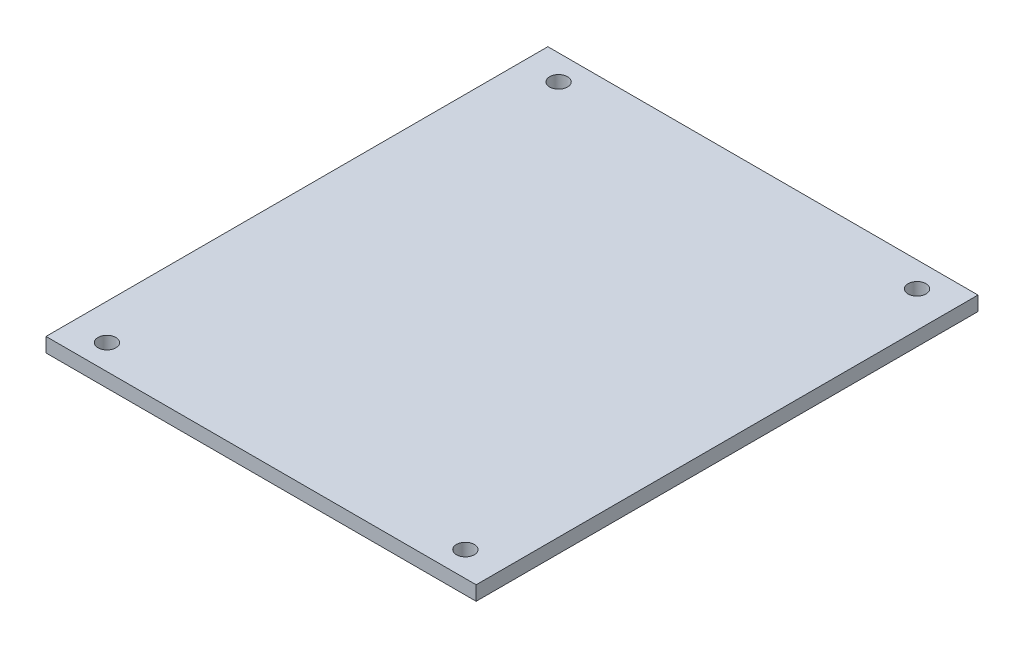
SolidWorks part; units mm, degrees
material "1060 Alloy"
ref_plane "Front Plane" through (0, 0, 0) normal (0, 0, 1) x (1, 0, 0)
ref_plane "Top Plane" through (0, 0, 0) normal (0, 1, 0) x (1, 0, 0)
ref_plane "Right Plane" through (0, 0, 0) normal (1, 0, 0) x (0, 0, -1)
sketch "Sketch1" plane through (0, 0, 0) normal (0, 1, 0) x (1, 0, 0)
  line L1 (-60, -70) -> (60, -70)
  line L2 (-60, -70) -> (-60, 70)
  line L3 (-60, 70) -> (60, 70)
  line L4 (60, -70) -> (60, 70)
  line L5 (-60, -70) -> (60, 70) construction
  line L6 (-60, 70) -> (60, -70) construction
  point P0 (0, 0)
  dimension "D1" = 140
  dimension "D2" = 120
extrude "Boss-Extrude1" add sketch "Sketch1" along normal blind 4
sketch "Sketch2" plane through (0, 4, 0) normal (0, 1, 0) x (1, 0, 0)
  line L0 (60, -70) -> (60, 70) construction
  line L1 (60, 50) -> (48, 50)
  line L2 (60, 50) -> (60, 27)
  line L3 (60, 27) -> (48, 27)
  line L4 (48, 50) -> (48, 27)
  line L5 (-60, 70) -> (-60, -70) construction
  line L6 (-60, 50) -> (-48, 50)
  line L7 (-60, 50) -> (-60, 27)
  line L8 (-60, 27) -> (-48, 27)
  line L9 (-48, 50) -> (-48, 27)
  line L10 (-48, 0) -> (0, 0) construction
  line L19 (60, -27) -> (48, -27)
  line L20 (60, -27) -> (60, -50)
  line L21 (60, -50) -> (48, -50)
  line L22 (48, -27) -> (48, -50)
  line L23 (-60, -27) -> (-48, -27)
  line L24 (-60, -27) -> (-60, -50)
  line L25 (-60, -50) -> (-48, -50)
  line L26 (-48, -27) -> (-48, -50)
  line L27 (0, 0) -> (48, 0) construction
  line L28 (-54, 52.65) -> (-54, 50) construction
  line L29 (-60, -70) -> (60, -70) construction
  line L30 (60, 70) -> (-60, 70) construction
  line L31 (-54, 24.35) -> (-54, 27) construction
  line L32 (-60, 17) -> (-48, 17)
  line L33 (-60, 17) -> (-60, -17)
  line L34 (-60, -17) -> (-48, -17)
  line L35 (-48, 17) -> (-48, -17)
  line L36 (60, 17) -> (48, 17)
  line L37 (60, 17) -> (60, -17)
  line L38 (60, -17) -> (48, -17)
  line L39 (48, 17) -> (48, -17)
  line L40 (-54, -24.35) -> (-54, -27) construction
  line L41 (-54, -50) -> (-54, -52.65) construction
  line L42 (54, 52.65) -> (54, 50) construction
  line L43 (54, 24.35) -> (54, 27) construction
  line L44 (54, -24.35) -> (54, -27) construction
  line L45 (54, -50) -> (54, -52.65) construction
  circle A2 centre (-54, 52.65) radius 1.1
  circle A3 centre (-54, 24.35) radius 1.1
  circle A4 centre (-54, -24.35) radius 1.1
  circle A5 centre (-54, -52.65) radius 1.1
  circle A6 centre (54, 52.65) radius 1.1
  circle A7 centre (54, 24.35) radius 1.1
  circle A8 centre (54, -24.35) radius 1.1
  circle A9 centre (54, -52.65) radius 1.1
  circle A10 centre (-50, 63) radius 2.5
  circle A11 centre (50, 63) radius 2.5
  circle A12 centre (50, -63) radius 2.5
  circle A13 centre (-50, -63) radius 2.5
  dimension "D6" = 2.2
  dimension "D15" = 5
  dimension "D1" = 23
  dimension "D2" = 12
  dimension "D3" = 20
  dimension "D4" = 20
  dimension "D5" = 10
  dimension "D7" = 2.65
  dimension "D8" = 2.65
  dimension "D9" = 2.65
  dimension "D10" = 2.65
  dimension "D11" = 2.65
  dimension "D12" = 2.65
  dimension "D13" = 2.65
  dimension "D14" = 2.65
  dimension "D16" = 10
  dimension "D17" = 7
  dimension "D18" = 7
  dimension "D19" = 10
  dimension "D20" = 10
  dimension "D21" = 7
  dimension "D22" = 10
  dimension "D23" = 7
extrude "Cut-Extrude1" cut sketch "Sketch2" against normal through all contours A10 | A11 | A13 | A12
